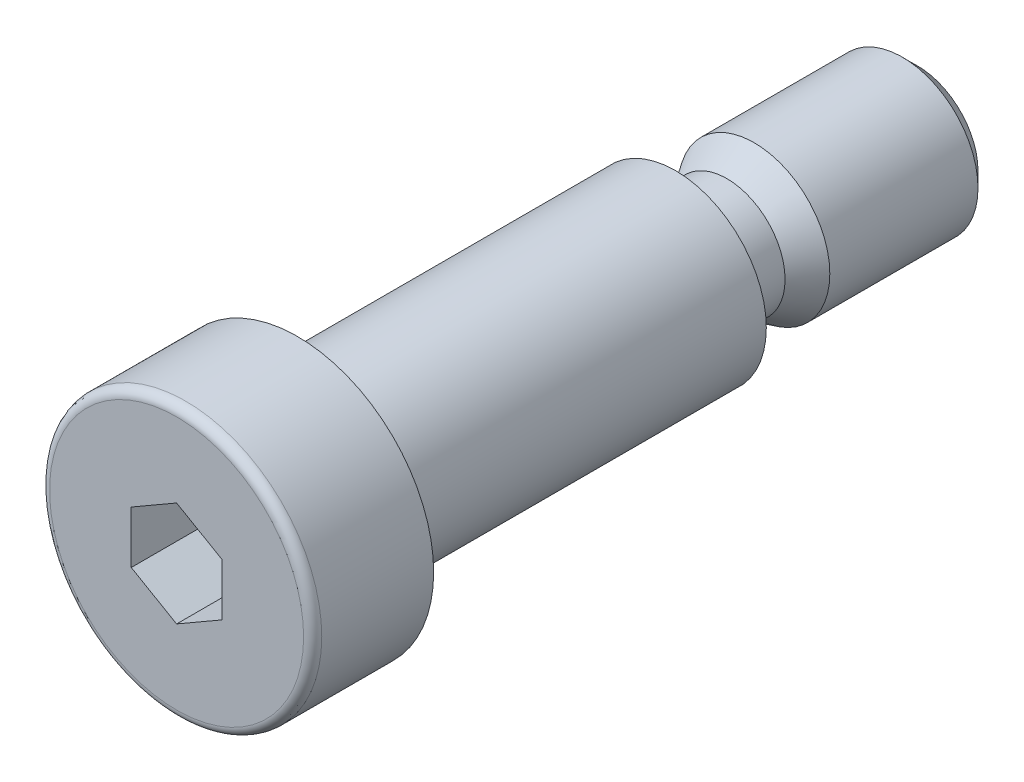
SolidWorks part; units mm, degrees
material "1.0545 (S355N)"
ref_plane "Płaszczyzna przednia" through (0, 0, 0) normal (0, 0, 1) x (1, 0, 0)
ref_plane "Płaszczyzna górna" through (0, 0, 0) normal (0, 1, 0) x (1, 0, 0)
ref_plane "Płaszczyzna prawa" through (0, 0, 0) normal (1, 0, 0) x (0, 0, -1)
sketch "Szkic1" plane through (0, 0, 0) normal (0, 1, 0) x (1, 0, 0)
  line L0 (5, 17.7) -> (3.85, 15.89)
  line L1 (9, -20.5) -> (-9, -20.5)
  line L2 (9, -20.5) -> (9, -12.5)
  line L3 (9, -12.5) -> (-9, -12.5)
  line L4 (-9, -20.5) -> (-9, -12.5)
  line L5 (6, -12.5) -> (-6, -12.5)
  line L6 (6, -12.5) -> (6, 12.5)
  line L7 (6, 12.5) -> (-6, 12.5)
  line L8 (-6, -12.5) -> (-6, 12.5)
  line L9 (-3.85, 12.5) -> (3.85, 12.5)
  line L10 (-3.85, 12.5) -> (-3.85, 15.89)
  line L11 (-3.85, 15.89) -> (3.85, 15.89)
  line L12 (3.85, 12.5) -> (3.85, 15.89)
  line L13 (5, 17.7) -> (5, 27.5)
  line L14 (5, 27.5) -> (4, 28.5)
  line L15 (4, 28.5) -> (-4, 28.5)
  line L16 (-4, 28.5) -> (-5, 27.5)
  line L17 (-5, 27.5) -> (-5, 17.7)
  line L18 (-5, 17.7) -> (-3.85, 15.89)
  line L19 (5, 17.7) -> (-5, 17.7) construction
  line L20 (5, 27.5) -> (-5, 27.5) construction
  line L21 (0, -19.9356) -> (0, 25.6583) construction
  line L22 (0, -20.5) -> (0, 28.5)
  point P4 (0, -12.5)
  point P14 (0, -12.5)
  point P15 (0, 12.5)
  point P16 (0, 12.5)
  point P17 (-6, 0)
  point P23 (0, 17.7)
  point P25 (0, 28.5)
  point P26 (0, 15.89)
  point P27 (0, 27.5)
  dimension "D1" = 18
  dimension "D2" = 8
  dimension "D3" = 12
  dimension "l1" = 25
  dimension "D5" = 7.7
  dimension "D6" = 16
  dimension "D7" = 10
  dimension "D8" = 8
  dimension "D9" = 1
  dimension "D10" = 1.81
  dimension "D11" = 9.8
revolve "Obrót1" add sketch "Szkic1" angle 360 about L22
sketch "Szkic2" plane through (0, 0, 20.5) normal (0, 0, 1) x (1, 0, 0)
  line L1 (3, 1.7321) -> (0, 3.4641)
  line L2 (0, 3.4641) -> (-3, 1.7321)
  line L3 (-3, 1.7321) -> (-3, -1.7321)
  line L4 (-3, -1.7321) -> (0, -3.4641)
  line L5 (0, -3.4641) -> (3, -1.7321)
  line L6 (3, -1.7321) -> (3, 1.7321)
  circle A0 centre (0, 0) radius 3 construction
  dimension "D1" = 6
extrude "Wytnij-wyciągnięcie1" cut sketch "Szkic2" against normal blind 4.9
fillet "Zaokrąglenie1" radius 0.6 1 edges at (9, 0, 20.5)
